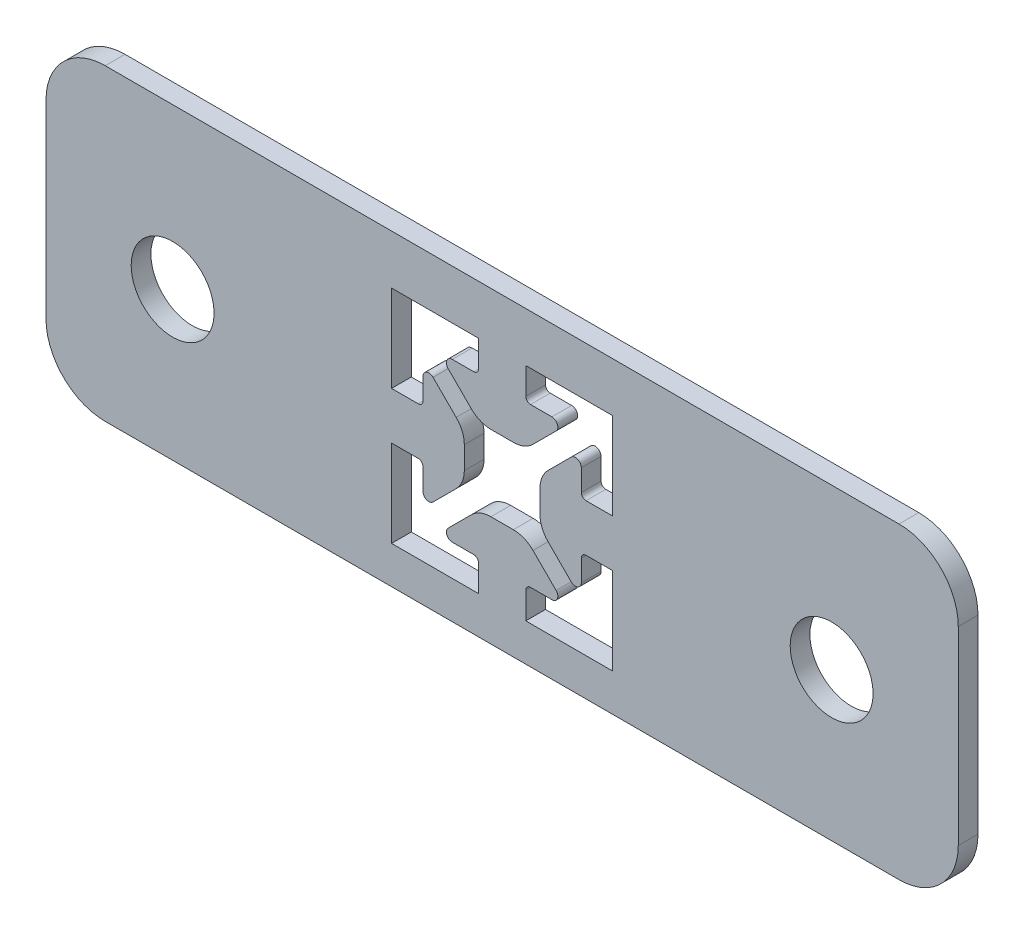
SolidWorks part; units mm, degrees
ref_plane "Front Plane" through (0, 0, 0) normal (0, 0, 1) x (1, 0, 0)
ref_plane "Top Plane" through (0, 0, 0) normal (0, 1, 0) x (1, 0, 0)
ref_plane "Right Plane" through (0, 0, 0) normal (1, 0, 0) x (0, 0, -1)
sketch "Sketch1" plane through (0, 0, 1287.7952) normal (0, 0, -1) x (-1, 0, 0)
  line L0 (-682.9917, 882.4939) -> (-685.6917, 882.4939) construction
  line L1 (-682.5117, 885.143) -> (-682.5117, 882.9739) construction
  line L2 (-679.1477, 883.2275) -> (-681.4874, 885.5673) construction
  line L3 (-678.3217, 878.9644) -> (-678.3217, 881.2335) construction
  line L4 (-681.4874, 874.6305) -> (-679.1477, 876.9703) construction
  line L5 (-682.5117, 877.2239) -> (-682.5117, 875.0548) construction
  line L6 (-685.6917, 877.7039) -> (-682.9917, 877.7039) construction
  line L7 (-685.6917, 868.8989) -> (-685.6917, 877.7039) construction
  line L8 (-676.8867, 868.8989) -> (-685.6917, 868.8989) construction
  line L9 (-676.8867, 871.5989) -> (-676.8867, 868.8989) construction
  line L10 (-679.5358, 872.0789) -> (-677.3667, 872.0789) construction
  line L11 (-677.6203, 875.443) -> (-679.9601, 873.1032) construction
  line L12 (-673.3571, 876.2689) -> (-675.6263, 876.2689) construction
  line L13 (-669.0233, 873.1032) -> (-671.3631, 875.443) construction
  line L14 (-671.6167, 872.0789) -> (-669.4476, 872.0789) construction
  line L15 (-672.0967, 868.8989) -> (-672.0967, 871.5989) construction
  line L16 (-663.2917, 868.8989) -> (-672.0967, 868.8989) construction
  line L17 (-663.2917, 877.7039) -> (-663.2917, 868.8989) construction
  line L18 (-665.9917, 877.7039) -> (-663.2917, 877.7039) construction
  line L19 (-666.4717, 875.0548) -> (-666.4717, 877.2239) construction
  line L20 (-669.8358, 876.9703) -> (-667.496, 874.6305) construction
  line L21 (-670.6617, 881.2335) -> (-670.6617, 878.9644) construction
  line L22 (-667.496, 885.5673) -> (-669.8358, 883.2275) construction
  line L23 (-666.4717, 882.9739) -> (-666.4717, 885.143) construction
  line L24 (-663.2917, 882.4939) -> (-665.9917, 882.4939) construction
  line L25 (-663.2917, 891.2989) -> (-663.2917, 882.4939) construction
  line L26 (-672.0967, 891.2989) -> (-663.2917, 891.2989) construction
  line L27 (-672.0967, 888.5989) -> (-672.0967, 891.2989) construction
  line L28 (-669.4476, 888.1189) -> (-671.6167, 888.1189) construction
  line L29 (-671.3631, 884.7549) -> (-669.0233, 887.0947) construction
  line L30 (-675.6263, 883.9289) -> (-673.3571, 883.9289) construction
  line L31 (-679.9601, 887.0947) -> (-677.6203, 884.7549) construction
  line L32 (-677.3667, 888.1189) -> (-679.5358, 888.1189) construction
  line L33 (-676.8867, 891.2989) -> (-676.8867, 888.5989) construction
  line L34 (-685.6917, 891.2989) -> (-676.8867, 891.2989) construction
  line L35 (-685.6917, 882.4939) -> (-685.6917, 891.2989) construction
  line L36 (-628.2917, 871.0989) -> (-628.2917, 890.2989) construction
  line L37 (-634.2917, 865.0989) -> (-714.6917, 865.0989) construction
  line L38 (-714.6917, 896.2989) -> (-634.2917, 896.2989) construction
  line L39 (-720.6917, 871.0989) -> (-720.6917, 890.2989) construction
  line L40 (-682.9917, 882.4939) -> (-685.6917, 882.4939)
  line L41 (-682.5117, 885.143) -> (-682.5117, 882.9739)
  line L42 (-679.1477, 883.2275) -> (-681.4874, 885.5673)
  line L43 (-678.3217, 878.9644) -> (-678.3217, 881.2335)
  line L44 (-681.4874, 874.6305) -> (-679.1477, 876.9703)
  line L45 (-682.5117, 877.2239) -> (-682.5117, 875.0548)
  line L46 (-685.6917, 877.7039) -> (-682.9917, 877.7039)
  line L47 (-685.6917, 868.8989) -> (-685.6917, 877.7039)
  line L48 (-676.8867, 868.8989) -> (-685.6917, 868.8989)
  line L49 (-676.8867, 871.5989) -> (-676.8867, 868.8989)
  line L50 (-679.5358, 872.0789) -> (-677.3667, 872.0789)
  line L51 (-677.6203, 875.443) -> (-679.9601, 873.1032)
  line L52 (-673.3571, 876.2689) -> (-675.6263, 876.2689)
  line L53 (-669.0233, 873.1032) -> (-671.3631, 875.443)
  line L54 (-671.6167, 872.0789) -> (-669.4476, 872.0789)
  line L55 (-672.0967, 868.8989) -> (-672.0967, 871.5989)
  line L56 (-663.2917, 868.8989) -> (-672.0967, 868.8989)
  line L57 (-663.2917, 877.7039) -> (-663.2917, 868.8989)
  line L58 (-665.9917, 877.7039) -> (-663.2917, 877.7039)
  line L59 (-666.4717, 875.0548) -> (-666.4717, 877.2239)
  line L60 (-669.8358, 876.9703) -> (-667.496, 874.6305)
  line L61 (-670.6617, 881.2335) -> (-670.6617, 878.9644)
  line L62 (-667.496, 885.5673) -> (-669.8358, 883.2275)
  line L63 (-666.4717, 882.9739) -> (-666.4717, 885.143)
  line L64 (-663.2917, 882.4939) -> (-665.9917, 882.4939)
  line L65 (-663.2917, 891.2989) -> (-663.2917, 882.4939)
  line L66 (-672.0967, 891.2989) -> (-663.2917, 891.2989)
  line L67 (-672.0967, 888.5989) -> (-672.0967, 891.2989)
  line L68 (-669.4476, 888.1189) -> (-671.6167, 888.1189)
  line L69 (-671.3631, 884.7549) -> (-669.0233, 887.0947)
  line L70 (-675.6263, 883.9289) -> (-673.3571, 883.9289)
  line L71 (-679.9601, 887.0947) -> (-677.6203, 884.7549)
  line L72 (-677.3667, 888.1189) -> (-679.5358, 888.1189)
  line L73 (-676.8867, 891.2989) -> (-676.8867, 888.5989)
  line L74 (-685.6917, 891.2989) -> (-676.8867, 891.2989)
  line L75 (-685.6917, 882.4939) -> (-685.6917, 891.2989)
  line L76 (-628.2917, 871.0989) -> (-628.2917, 890.2989)
  line L77 (-634.2917, 865.0989) -> (-714.6917, 865.0989)
  line L78 (-714.6917, 896.2989) -> (-634.2917, 896.2989)
  line L79 (-720.6917, 871.0989) -> (-720.6917, 890.2989)
  arc A0 (-682.9917, 882.4939) -> (-682.5117, 882.9739) centre (-682.9917, 882.9739) ccw construction
  arc A1 (-681.4874, 885.5673) -> (-682.5117, 885.143) centre (-681.9117, 885.143) ccw construction
  arc A2 (-678.3217, 881.2335) -> (-679.1477, 883.2275) centre (-681.1417, 881.2335) ccw construction
  arc A3 (-679.1477, 876.9703) -> (-678.3217, 878.9644) centre (-681.1417, 878.9644) ccw construction
  arc A4 (-682.5117, 875.0548) -> (-681.4874, 874.6305) centre (-681.9117, 875.0548) ccw construction
  arc A5 (-682.5117, 877.2239) -> (-682.9917, 877.7039) centre (-682.9917, 877.2239) ccw construction
  arc A6 (-676.8867, 871.5989) -> (-677.3667, 872.0789) centre (-677.3667, 871.5989) ccw construction
  arc A7 (-679.9601, 873.1032) -> (-679.5358, 872.0789) centre (-679.5358, 872.6789) ccw construction
  arc A8 (-675.6263, 876.2689) -> (-677.6203, 875.443) centre (-675.6263, 873.4489) ccw construction
  arc A9 (-671.3631, 875.443) -> (-673.3571, 876.2689) centre (-673.3571, 873.4489) ccw construction
  arc A10 (-669.4476, 872.0789) -> (-669.0233, 873.1032) centre (-669.4476, 872.6789) ccw construction
  arc A11 (-671.6167, 872.0789) -> (-672.0967, 871.5989) centre (-671.6167, 871.5989) ccw construction
  arc A12 (-665.9917, 877.7039) -> (-666.4717, 877.2239) centre (-665.9917, 877.2239) ccw construction
  arc A13 (-667.496, 874.6305) -> (-666.4717, 875.0548) centre (-667.0717, 875.0548) ccw construction
  arc A14 (-670.6617, 878.9644) -> (-669.8358, 876.9703) centre (-667.8417, 878.9644) ccw construction
  arc A15 (-669.8358, 883.2275) -> (-670.6617, 881.2335) centre (-667.8417, 881.2335) ccw construction
  arc A16 (-666.4717, 885.143) -> (-667.496, 885.5673) centre (-667.0717, 885.143) ccw construction
  arc A17 (-666.4717, 882.9739) -> (-665.9917, 882.4939) centre (-665.9917, 882.9739) ccw construction
  arc A18 (-672.0967, 888.5989) -> (-671.6167, 888.1189) centre (-671.6167, 888.5989) ccw construction
  arc A19 (-669.0233, 887.0947) -> (-669.4476, 888.1189) centre (-669.4476, 887.5189) ccw construction
  arc A20 (-673.3571, 883.9289) -> (-671.3631, 884.7549) centre (-673.3571, 886.7489) ccw construction
  arc A21 (-677.6203, 884.7549) -> (-675.6263, 883.9289) centre (-675.6263, 886.7489) ccw construction
  arc A22 (-679.5358, 888.1189) -> (-679.9601, 887.0947) centre (-679.5358, 887.5189) ccw construction
  arc A23 (-677.3667, 888.1189) -> (-676.8867, 888.5989) centre (-677.3667, 888.5989) ccw construction
  circle A24 centre (-707.8667, 880.0989) radius 4.1985 construction
  circle A25 centre (-641.1167, 880.0989) radius 4.1985 construction
  arc A26 (-628.2917, 890.2989) -> (-634.2917, 896.2989) centre (-634.2917, 890.2989) ccw construction
  arc A27 (-634.2917, 865.0989) -> (-628.2917, 871.0989) centre (-634.2917, 871.0989) ccw construction
  arc A28 (-720.6917, 871.0989) -> (-714.6917, 865.0989) centre (-714.6917, 871.0989) ccw construction
  arc A29 (-714.6917, 896.2989) -> (-720.6917, 890.2989) centre (-714.6917, 890.2989) ccw construction
  arc A30 (-682.9917, 882.4939) -> (-682.5117, 882.9739) centre (-682.9917, 882.9739) ccw
  arc A31 (-681.4874, 885.5673) -> (-682.5117, 885.143) centre (-681.9117, 885.143) ccw
  arc A32 (-678.3217, 881.2335) -> (-679.1477, 883.2275) centre (-681.1417, 881.2335) ccw
  arc A33 (-679.1477, 876.9703) -> (-678.3217, 878.9644) centre (-681.1417, 878.9644) ccw
  arc A34 (-682.5117, 875.0548) -> (-681.4874, 874.6305) centre (-681.9117, 875.0548) ccw
  arc A35 (-682.5117, 877.2239) -> (-682.9917, 877.7039) centre (-682.9917, 877.2239) ccw
  arc A36 (-676.8867, 871.5989) -> (-677.3667, 872.0789) centre (-677.3667, 871.5989) ccw
  arc A37 (-679.9601, 873.1032) -> (-679.5358, 872.0789) centre (-679.5358, 872.6789) ccw
  arc A38 (-675.6263, 876.2689) -> (-677.6203, 875.443) centre (-675.6263, 873.4489) ccw
  arc A39 (-671.3631, 875.443) -> (-673.3571, 876.2689) centre (-673.3571, 873.4489) ccw
  arc A40 (-669.4476, 872.0789) -> (-669.0233, 873.1032) centre (-669.4476, 872.6789) ccw
  arc A41 (-671.6167, 872.0789) -> (-672.0967, 871.5989) centre (-671.6167, 871.5989) ccw
  arc A42 (-665.9917, 877.7039) -> (-666.4717, 877.2239) centre (-665.9917, 877.2239) ccw
  arc A43 (-667.496, 874.6305) -> (-666.4717, 875.0548) centre (-667.0717, 875.0548) ccw
  arc A44 (-670.6617, 878.9644) -> (-669.8358, 876.9703) centre (-667.8417, 878.9644) ccw
  arc A45 (-669.8358, 883.2275) -> (-670.6617, 881.2335) centre (-667.8417, 881.2335) ccw
  arc A46 (-666.4717, 885.143) -> (-667.496, 885.5673) centre (-667.0717, 885.143) ccw
  arc A47 (-666.4717, 882.9739) -> (-665.9917, 882.4939) centre (-665.9917, 882.9739) ccw
  arc A48 (-672.0967, 888.5989) -> (-671.6167, 888.1189) centre (-671.6167, 888.5989) ccw
  arc A49 (-669.0233, 887.0947) -> (-669.4476, 888.1189) centre (-669.4476, 887.5189) ccw
  arc A50 (-673.3571, 883.9289) -> (-671.3631, 884.7549) centre (-673.3571, 886.7489) ccw
  arc A51 (-677.6203, 884.7549) -> (-675.6263, 883.9289) centre (-675.6263, 886.7489) ccw
  arc A52 (-679.5358, 888.1189) -> (-679.9601, 887.0947) centre (-679.5358, 887.5189) ccw
  arc A53 (-677.3667, 888.1189) -> (-676.8867, 888.5989) centre (-677.3667, 888.5989) ccw
  circle A54 centre (-707.8667, 880.0989) radius 4.1985
  circle A55 centre (-641.1167, 880.0989) radius 4.1985
  arc A56 (-628.2917, 890.2989) -> (-634.2917, 896.2989) centre (-634.2917, 890.2989) ccw
  arc A57 (-634.2917, 865.0989) -> (-628.2917, 871.0989) centre (-634.2917, 871.0989) ccw
  arc A58 (-720.6917, 871.0989) -> (-714.6917, 865.0989) centre (-714.6917, 871.0989) ccw
  arc A59 (-714.6917, 896.2989) -> (-720.6917, 890.2989) centre (-714.6917, 890.2989) ccw
extrude "Boss-Extrude1" add sketch "Sketch1" along normal blind 2
